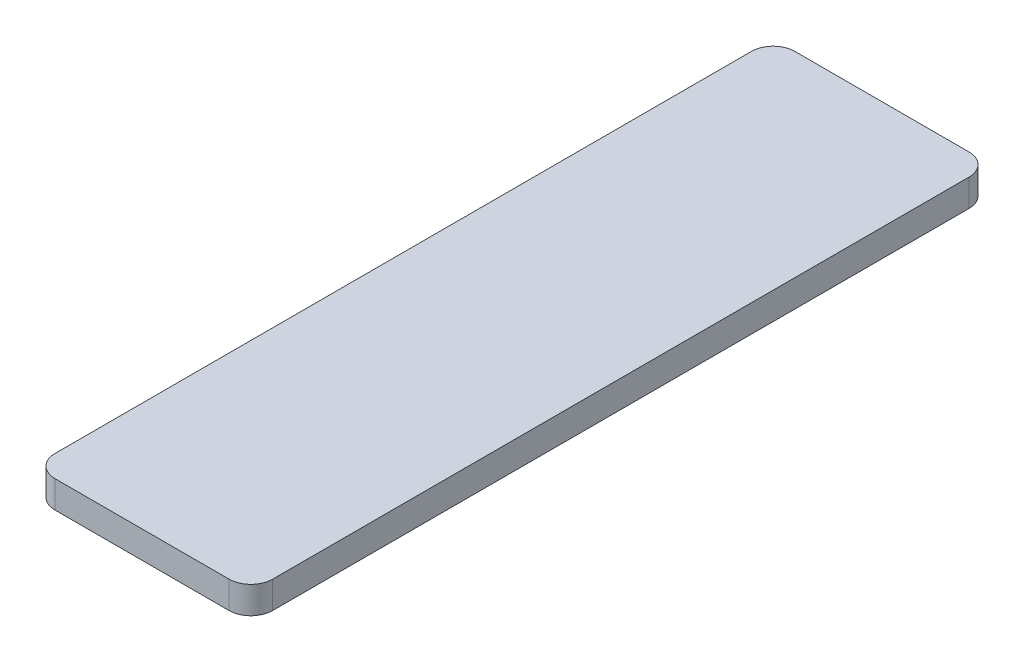
SolidWorks part; units mm, degrees
material "Acrylic (Medium-high impact)"
ref_plane "Front Plane" through (0, 0, 0) normal (0, 0, 1) x (1, 0, 0)
ref_plane "Top Plane" through (0, 0, 0) normal (0, 1, 0) x (1, 0, 0)
ref_plane "Right Plane" through (0, 0, 0) normal (1, 0, 0) x (0, 0, -1)
ref_plane "Plane1" through (0, 0, 0) normal (0, 1, 0) x (1, 0, 0)
sketch "Sketch1" plane through (0, 0, 0) normal (0, 1, 0) x (1, 0, 0)
  line L1 (-26.2811, -30.1338) -> (-0.8811, -30.1338)
  line L2 (-26.2811, -30.1338) -> (-26.2811, 56.2162)
  line L3 (-26.2811, 56.2162) -> (-0.8811, 56.2162)
  line L4 (-0.8811, -30.1338) -> (-0.8811, 56.2162)
  dimension "D1" = 86.35
  dimension "D2" = 25.4
extrude "Boss-Extrude1" add sketch "Sketch1" along normal blind 3.175
fillet "Fillet1" radius 2.54 4 edges at (-26.2811, 1.5875, -56.2162) (-0.8811, 1.5875, -56.2162) (-0.8811, 1.5875, 30.1338) (-26.2811, 1.5875, 30.1338)
